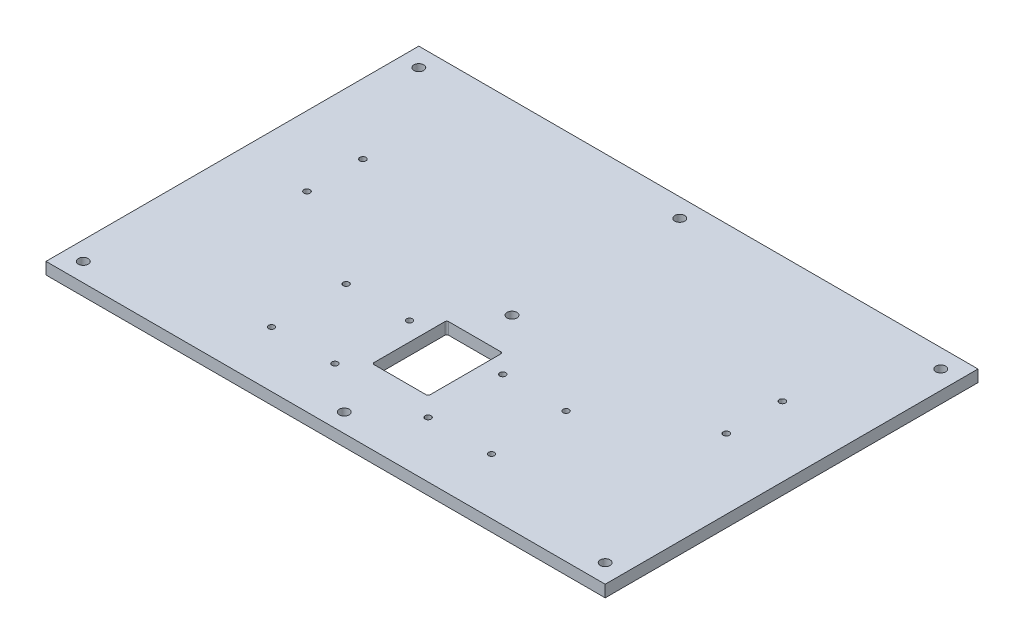
SolidWorks part; units mm, degrees
material "Acrylic (Medium-high impact)"
ref_plane "Front Plane" through (0, 0, 0) normal (0, 0, 1) x (1, 0, 0)
ref_plane "Top Plane" through (0, 0, 0) normal (0, 1, 0) x (1, 0, 0)
ref_plane "Right Plane" through (0, 0, 0) normal (1, 0, 0) x (0, 0, -1)
sketch "Sketch1" plane through (0, 0, 0) normal (0, 1, 0) x (1, 0, 0)
  line L0 (-112.5, 32.5) -> (-112.5, 2.5) construction
  line L1 (-150, 100) -> (150, 100)
  line L2 (-150, 100) -> (-150, -100)
  line L3 (-150, -100) -> (150, -100)
  line L4 (150, 100) -> (150, -100)
  line L5 (-140, 90) -> (140, 90) construction
  line L6 (-140, 90) -> (-140, -90) construction
  line L7 (-140, -90) -> (140, -90) construction
  line L8 (140, 90) -> (140, -90) construction
  line L9 (-59, -30) -> (-25, -30) construction
  line L10 (-59, -30) -> (-59, -70) construction
  line L11 (-59, -70) -> (-25, -70) construction
  line L12 (-25, -30) -> (-25, -70) construction
  line L13 (0, 90) -> (0, -90) construction
  line L15 (-155, 67.5) -> (-70, 67.5) construction
  line L16 (-155, 67.5) -> (-155, -67.5) construction
  line L17 (-155, -67.5) -> (-70, -67.5) construction
  line L18 (-70, 67.5) -> (-70, -67.5) construction
  line L19 (-15, -20) -> (15, -20)
  line L20 (-15, -20) -> (-15, -60)
  line L21 (-15, -60) -> (15, -60)
  line L22 (15, -20) -> (15, -60)
  circle A0 centre (-140, 90) radius 2.5 construction
  circle A1 centre (0, 90) radius 2.5 construction
  circle A2 centre (140, 90) radius 2.5 construction
  circle A3 centre (140, -90) radius 2.5 construction
  circle A4 centre (0, -90) radius 2.5 construction
  circle A5 centre (-140, -90) radius 2.5 construction
  circle A6 centre (-59, -30) radius 1.5 construction
  circle A7 centre (-25, -30) radius 1.5 construction
  circle A8 centre (-25, -70) radius 1.5 construction
  circle A9 centre (-59, -70) radius 1.5 construction
  circle A10 centre (-112.5, 2.5) radius 2 construction
  circle A11 centre (-112.5, 32.5) radius 2 construction
  circle A12 centre (59, -70) radius 1.5 construction
  circle A13 centre (25, -70) radius 1.5 construction
  circle A14 centre (25, -30) radius 1.5 construction
  circle A15 centre (59, -30) radius 1.5 construction
  circle A16 centre (112.5, 2.5) radius 2 construction
  circle A17 centre (112.5, 32.5) radius 2 construction
  circle A18 centre (0, 0) radius 2.5 construction
  point P4 (0, 100)
  point P6 (-150, 0)
  point P11 (0, 90)
  point P20 (-140, 0)
  point P39 (-112.5, 67.5)
  point P44 (-70, 0)
  point P45 (0, -20)
  dimension "D5" = 5
  dimension "D6" = 4
  dimension "D7" = 3
  dimension "D16" = 5
  dimension "D1" = 200
  dimension "D2" = 300
  dimension "D3" = 10
  dimension "D4" = 10
  dimension "D8" = 30
  dimension "D9" = 35
  dimension "D10" = 85
  dimension "D11" = 135
  dimension "D12" = 40
  dimension "D13" = 34
  dimension "D14" = 25
  dimension "D15" = 20
  dimension "D17" = 112.5
  dimension "D18" = 30
  dimension "D19" = 40
  dimension "D20" = 80
extrude "Boss-Extrude1" add sketch "Sketch1" against normal blind 6.35
hole_wizard "Tap Drill for M4x0.7 Tap1" positions "3DSketch1" profile "Sketch2" hole size "M4x0.7" standard "ANSI Metric" end condition up to next
sketch3d "3DSketch1"
  point P20 (-112.5, 0, -32.5)
  point P22 (-112.5, 0, -2.5)
  point P24 (112.5, 0, -32.5)
  point P26 (112.5, 0, -2.5)
  point P29 (112.5, 0, -2.5)
  point P31 (112.5, 0, -32.5)
  point P33 (-112.5, 0, -32.5)
  point P35 (-112.5, 0, -2.5)
sketch "Sketch2" plane through (-112.5, 0, -32.5) normal (1, 0, 0) x (0, 0, 1)
  line L0 (0, 0) -> (0, 6.35)
  line L1 (0, 6.35) -> (1.65, 6.35)
  line L2 (1.65, 6.35) -> (1.65, 0)
  line L5 (1.65, 0) -> (0, 0)
  line L11 (0, -6.35) -> (0, 107.95) construction
  dimension "Thru Hole Dia." = 3.3
  dimension "Thru Hole Depth" = 6.35
hole_wizard "M3 Clearance Hole1" positions "3DSketch2" profile "Sketch3" hole size "M3" standard "ANSI Metric" end condition up to next
sketch3d "3DSketch2"
  point P34 (-59, 0, 30)
  point P36 (-25, 0, 30)
  point P38 (-59, 0, 70)
  point P40 (-25, 0, 70)
  point P42 (25, 0, 30)
  point P44 (59, 0, 30)
  point P46 (25, 0, 70)
  point P48 (59, 0, 70)
  point P51 (25, 0, 30)
  point P53 (59, 0, 30)
  point P55 (59, 0, 70)
  point P57 (25, 0, 70)
  point P59 (-59, 0, 30)
  point P61 (-25, 0, 30)
  point P63 (-25, 0, 70)
  point P65 (-59, 0, 70)
sketch "Sketch3" plane through (-59, 0, 30) normal (1, 0, 0) x (0, 0, 1)
  line L0 (0, 0) -> (0, 6.35)
  line L1 (0, 6.35) -> (1.6, 6.35)
  line L2 (1.6, 6.35) -> (1.6, 0)
  line L5 (1.6, 0) -> (0, 0)
  line L11 (0, -6.35) -> (0, 107.95) construction
  dimension "Thru Hole Dia." = 3.2
  dimension "Thru Hole Depth" = 6.35
hole_wizard "M5 Clearance Hole1" positions "3DSketch3" profile "Sketch4" hole size "M5" standard "ANSI Metric" end condition up to next
sketch3d "3DSketch3"
  point P31 (-140, 0, -90)
  point P33 (0, 0, -90)
  point P35 (140, 0, -90)
  point P37 (140, 0, 90)
  point P39 (0, 0, 90)
  point P41 (-140, 0, 90)
  point P56 (0, 0, 0)
  point P59 (8.1403, 0, 6.555)
  point P60 (0, 0, 0)
sketch "Sketch4" plane through (-140, 0, -90) normal (1, 0, 0) x (0, 0, 1)
  line L0 (0, 0) -> (0, 6.35)
  line L1 (0, 6.35) -> (2.65, 6.35)
  line L2 (2.65, 6.35) -> (2.65, 0)
  line L5 (2.65, 0) -> (0, 0)
  line L11 (0, -6.35) -> (0, 107.95) construction
  dimension "Thru Hole Dia." = 5.3
  dimension "Thru Hole Depth" = 6.35
fillet "Fillet1" radius 1 4 edges at (15, -3.175, 20) (15, -3.175, 60) (-15, -3.175, 60) (-15, -3.175, 20)
